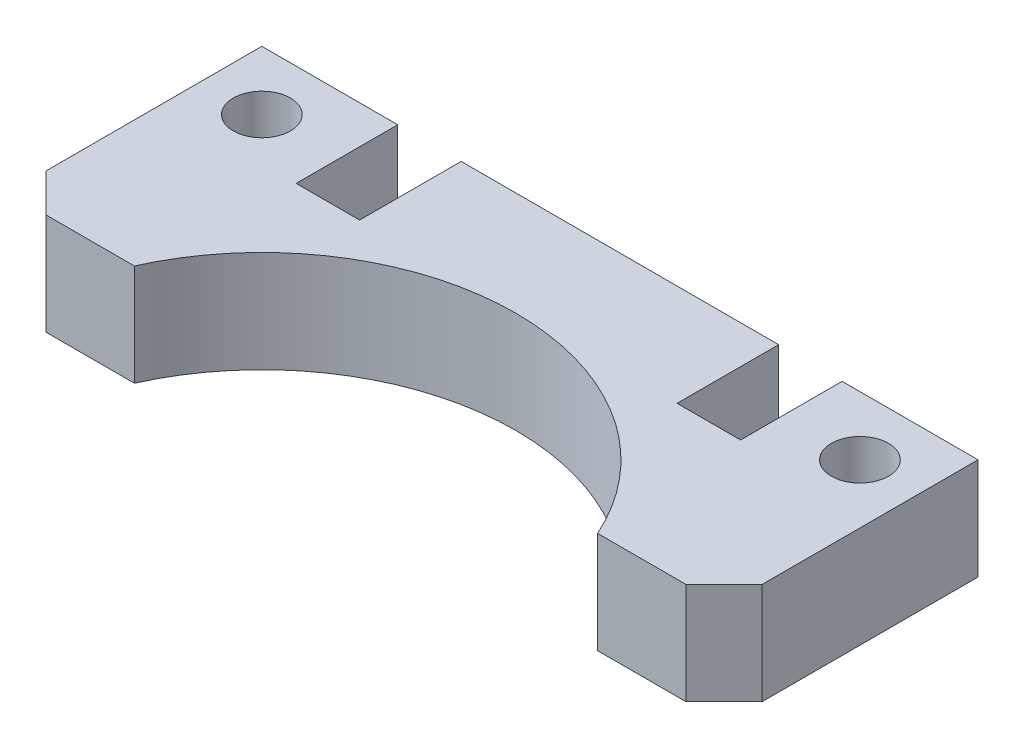
SolidWorks part; units mm, degrees
ref_plane "정면" through (0, 0, 0) normal (0, 0, 1) x (1, 0, 0)
ref_plane "윗면" through (0, 0, 0) normal (0, 1, 0) x (1, 0, 0)
ref_plane "우측면" through (0, 0, 0) normal (1, 0, 0) x (0, 0, -1)
sketch "스케치1" plane through (0, 0, 0) normal (0, 1, 0) x (1, 0, 0)
  line L1 (0, 0) -> (56.4, 0)
  line L2 (0, 0) -> (0, 20)
  line L3 (0, 20) -> (56.4, 20)
  line L4 (56.4, 0) -> (56.4, 20)
  dimension "D1" = 56.4
  dimension "D2" = 20
extrude "보스-돌출1" add sketch "스케치1" along normal blind 8
sketch "스케치2" plane through (0, 8, 0) normal (0, 1, 0) x (1, 0, 0)
  line L0 (0, 15.35) -> (4.65, 15.35) construction
  line L1 (0, 20) -> (0, 0) construction
  line L2 (4.65, 15.35) -> (51.75, 15.35) construction
  line L3 (51.75, 15.35) -> (56.4, 15.35) construction
  line L4 (56.4, 0) -> (56.4, 20) construction
  line L9 (51.75, 15.35) -> (51.75, 20) construction
  line L10 (56.4, 20) -> (0, 20) construction
  circle A0 centre (51.75, 15.35) radius 2.25
  circle A1 centre (4.65, 15.35) radius 2.25
  dimension "D3" = 4.5
  dimension "D1" = 47.1
extrude "컷-돌출1" cut sketch "스케치2" against normal blind 8
chamfer "모따기1" distance 3 angle 45 2 edges at (56.4, 4, 0) (0, 4, 0)
sketch "스케치3" plane through (0, 8, 0) normal (0, 1, 0) x (1, 0, 0)
  line L0 (28.2, 20) -> (28.2, -8.2) construction
  line L1 (56.4, 20) -> (0, 20) construction
  circle A0 centre (28.2, -8.2) radius 20
  dimension "D2" = 40
  dimension "D1" = 28.2
extrude "컷-돌출2" cut sketch "스케치3" against normal blind 8
sketch "스케치4" plane through (0, 8, 0) normal (0, 1, 0) x (1, 0, 0)
  line L0 (56.4, 20) -> (0, 20) construction
  line L1 (10.7, 20) -> (15.7, 20)
  line L2 (10.7, 20) -> (10.7, 12)
  line L3 (10.7, 12) -> (15.7, 12)
  line L4 (15.7, 20) -> (15.7, 12)
  line L5 (45.7, 12) -> (56.4, 12) construction
  line L6 (40.7, 20) -> (45.7, 20)
  line L7 (40.7, 20) -> (40.7, 12)
  line L8 (40.7, 12) -> (45.7, 12)
  line L9 (45.7, 20) -> (45.7, 12)
  line L10 (56.4, 3) -> (56.4, 20) construction
  line L11 (10.7, 12) -> (0, 12) construction
  line L12 (0, 20) -> (0, 3) construction
  dimension "D1" = 8
  dimension "D2" = 8
  dimension "D3" = 5
  dimension "D4" = 5
  dimension "D5" = 25
extrude "컷-돌출3" cut sketch "스케치4" against normal blind 8
